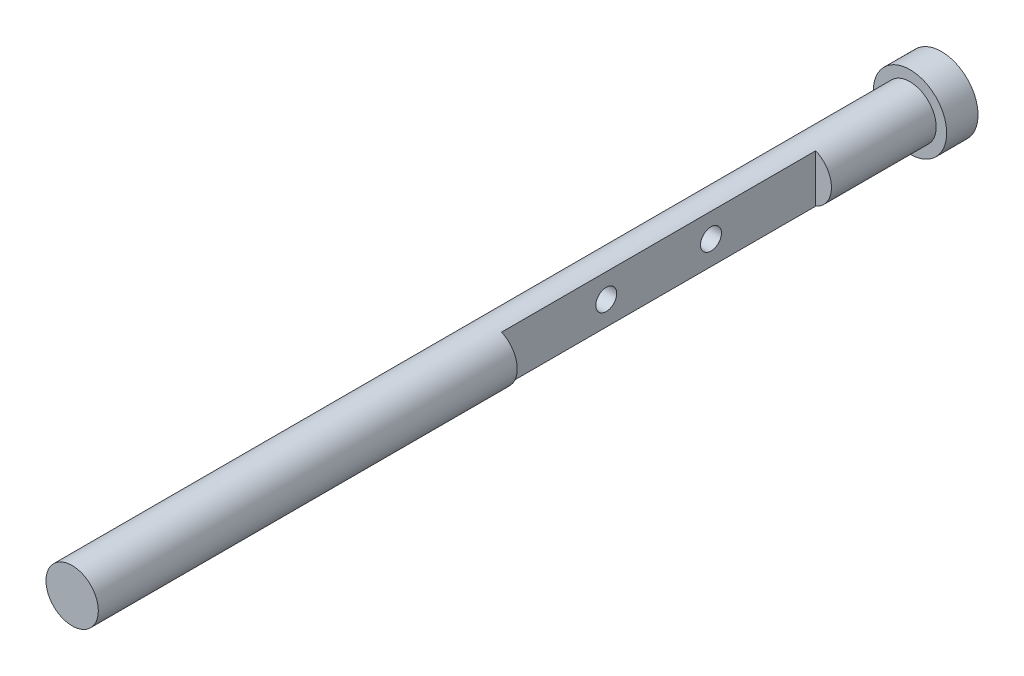
SolidWorks part; units mm, degrees
ref_plane "Plan de face" through (0, 0, 0) normal (0, 0, 1) x (1, 0, 0)
ref_plane "Plan de dessus" through (0, 0, 0) normal (0, 1, 0) x (1, 0, 0)
ref_plane "Plan de droite" through (0, 0, 0) normal (1, 0, 0) x (0, 0, -1)
sketch "Esquisse1" plane through (0, 0, 0) normal (0, 0, 1) x (1, 0, 0)
  circle A0 centre (0, 0) radius 2.5
  dimension "D1" = 5
extrude "Boss.-Extru.1" add sketch "Esquisse1" along normal blind 80
sketch "Esquisse2" plane through (0, 0, 0) normal (0, 0, -1) x (-1, 0, 0)
  circle A0 centre (0, 0) radius 3.5
  dimension "D1" = 7
extrude "Boss.-Extru.2" add sketch "Esquisse2" along normal blind 3
ref_plane "Plan1" through (1, 0, 0) normal (1, 0, 0) x (0, 0, -1)
sketch "Esquisse3" plane through (1, 0, 0) normal (1, 0, 0) x (0, 0, -1)
  line L0 (0, 2.5) -> (-80, 2.5) construction
  line L1 (-10, 2.5) -> (-40, 2.5)
  line L2 (-10, 2.5) -> (-10, -2.5)
  line L3 (-10, -2.5) -> (-40, -2.5)
  line L4 (-40, 2.5) -> (-40, -2.5)
  line L5 (-80, -2.5) -> (0, -2.5) construction
  line L6 (0, 2.5) -> (0, -2.5) construction
  dimension "D1" = 10
  dimension "D2" = 30
extrude "Enlèv. mat.-Extru.1" cut sketch "Esquisse3" along normal blind 3
sketch "Esquisse4" plane through (1, 0, 0) normal (1, 0, 0) x (0, 0, -1)
  line L0 (-10, 0) -> (-40, 0) construction
  line L2 (-40, -2.2913) -> (-40, 2.2913) construction
  line L3 (-10, -2.2913) -> (-10, 2.2913) construction
  line L4 (-10, 2.2913) -> (-10, -2.2913) construction
  circle A0 centre (-30, 0) radius 1
  circle A1 centre (-20, 0) radius 1
  point P6 (-10, 0)
  dimension "D1" = 2
  dimension "D2" = 2
  dimension "D3" = 10
  dimension "D4" = 10
extrude "Enlèv. mat.-Extru.2" cut sketch "Esquisse4" against normal blind 1.5
ref_plane "Plan2" through (0, -2.5, 0) normal (0, -1, 0) x (-1, 0, 0)
